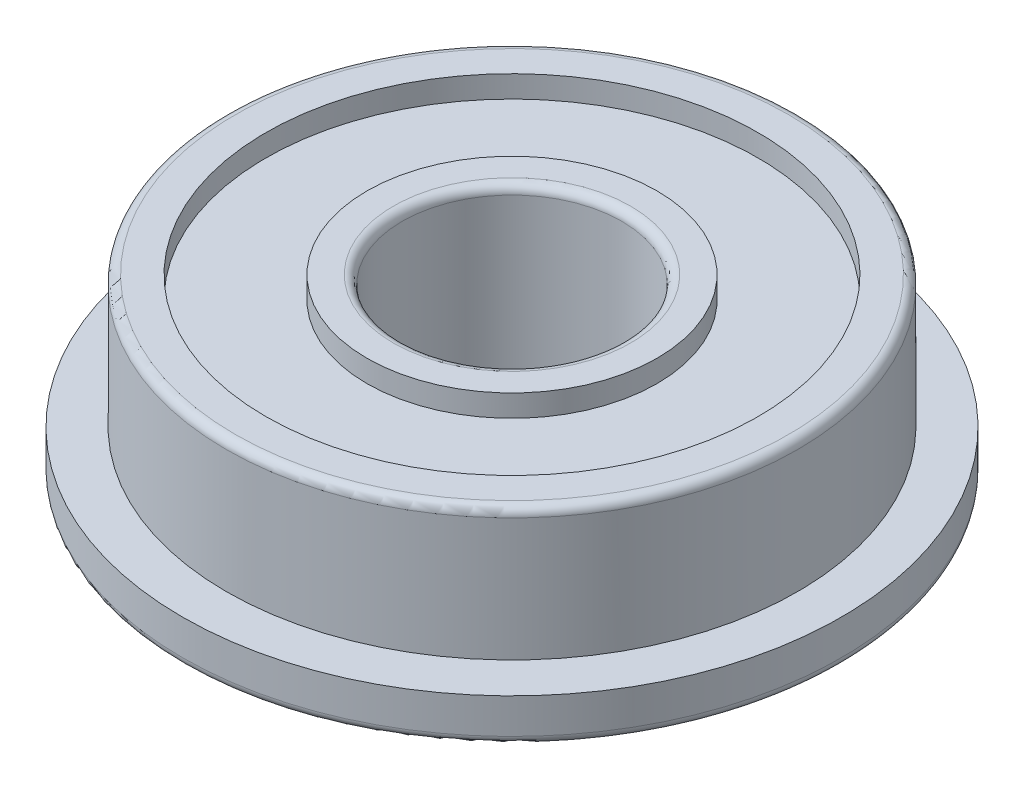
SolidWorks part; units mm, degrees
material "不锈钢 (铁素体)"
ref_plane "前视基准面" through (0, 0, 0) normal (0, 0, 1) x (1, 0, 0)
ref_plane "上视基准面" through (0, 0, 0) normal (0, 1, 0) x (1, 0, 0)
ref_plane "右视基准面" through (0, 0, 0) normal (1, 0, 0) x (0, 0, -1)
sketch "草图1" plane through (0, 0, 0) normal (0, 0, 1) x (1, 0, 0)
  line L0 (0, 5.4122) -> (0, -4.3124) construction
  line L1 (-5.1861, 0) -> (6.8276, 0) construction
  line L2 (2.5, 0) -> (7.5, 0)
  line L3 (7.5, 0) -> (7.5, 1)
  line L4 (7.5, 1) -> (6.5, 1)
  line L5 (6.5, 1) -> (6.5, 4)
  line L6 (6.5, 4) -> (5.6, 4)
  line L7 (5.6, 4) -> (5.6, 3.5)
  line L8 (5.6, 3.5) -> (3.3, 3.5)
  line L9 (3.3, 3.5) -> (3.3, 4)
  line L10 (3.3, 4) -> (2.5, 4)
  line L11 (2.5, 4) -> (2.5, 0)
  line L12 (2.5, 2) -> (6.9921, 2) construction
  line L13 (5.6, 0) -> (5.6, 0.5)
  line L14 (5.6, 0.5) -> (3.3, 0.5)
  line L15 (3.3, 0.5) -> (3.3, 0)
  dimension "D1" = 5
  dimension "D2" = 6.6
  dimension "D3" = 11.2
  dimension "D4" = 13
  dimension "D5" = 15
  dimension "D6" = 1
  dimension "D7" = 4
  dimension "D8" = 0.5
revolve "旋转1" add sketch "草图1" angle 360 about L0
fillet "圆角1" radius 0.2 4 edges at (0, 0, 2.5) (0, 0, 7.5) (0, 4, 6.5) (0, 4, 2.5)
move or copy body "实体-移动/复制1" [suppressed] bodies to move or copy 106
